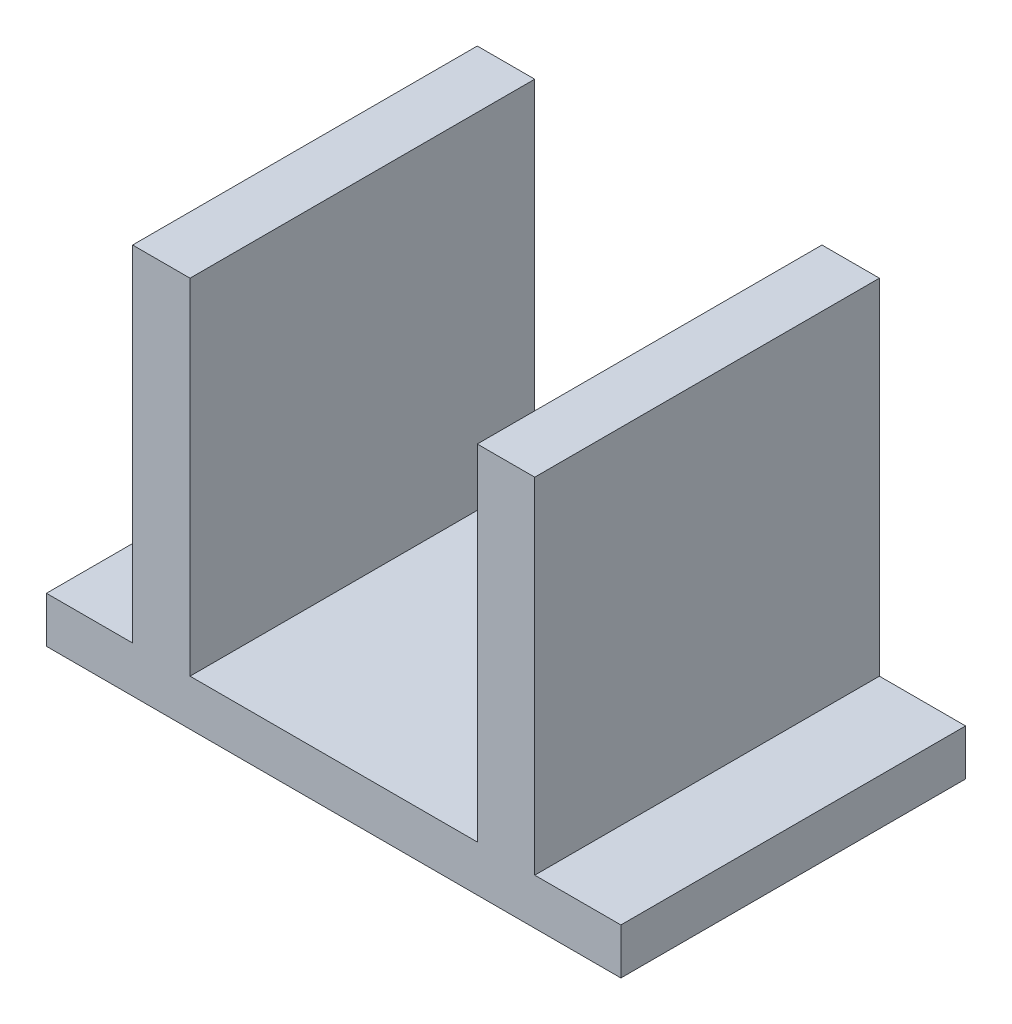
SolidWorks part; units mm, degrees
ref_plane "Front Plane" through (0, 0, 0) normal (0, 0, 1) x (1, 0, 0)
ref_plane "Top Plane" through (0, 0, 0) normal (0, 1, 0) x (1, 0, 0)
ref_plane "Right Plane" through (0, 0, 0) normal (1, 0, 0) x (0, 0, -1)
sketch "Sketch2" plane through (0, 0, 0) normal (0, 1, 0) x (1, 0, 0)
  line L1 (50, 30) -> (-50, 30)
  line L2 (50, 30) -> (50, -30)
  line L3 (50, -30) -> (-50, -30)
  line L4 (-50, 30) -> (-50, -30)
  line L5 (50, 30) -> (-50, -30) construction
  line L6 (50, -30) -> (-50, 30) construction
  point P0 (0, 0)
  dimension "D1" = 100
  dimension "D2" = 60
extrude "Boss-Extrude1" add sketch "Sketch2" along normal blind 8
sketch "Sketch3" plane through (0, 8, 0) normal (0, 1, 0) x (1, 0, 0)
  line L0 (50, 30) -> (-50, 30) construction
  line L1 (35, 30) -> (25, 30)
  line L2 (35, 30) -> (35, -30)
  line L3 (35, -30) -> (25, -30)
  line L4 (25, 30) -> (25, -30)
  line L5 (-50, -30) -> (50, -30) construction
  line L6 (50, -30) -> (50, 30) construction
  line L7 (0, 0) -> (0, 22.8812) construction
  line L8 (-35, -30) -> (-25, -30)
  line L9 (-25, 30) -> (-25, -30)
  line L10 (-35, 30) -> (-25, 30)
  line L11 (-35, 30) -> (-35, -30)
  dimension "D1" = 15
  dimension "D2" = 10
extrude "Boss-Extrude3" add sketch "Sketch3" along normal blind 60
